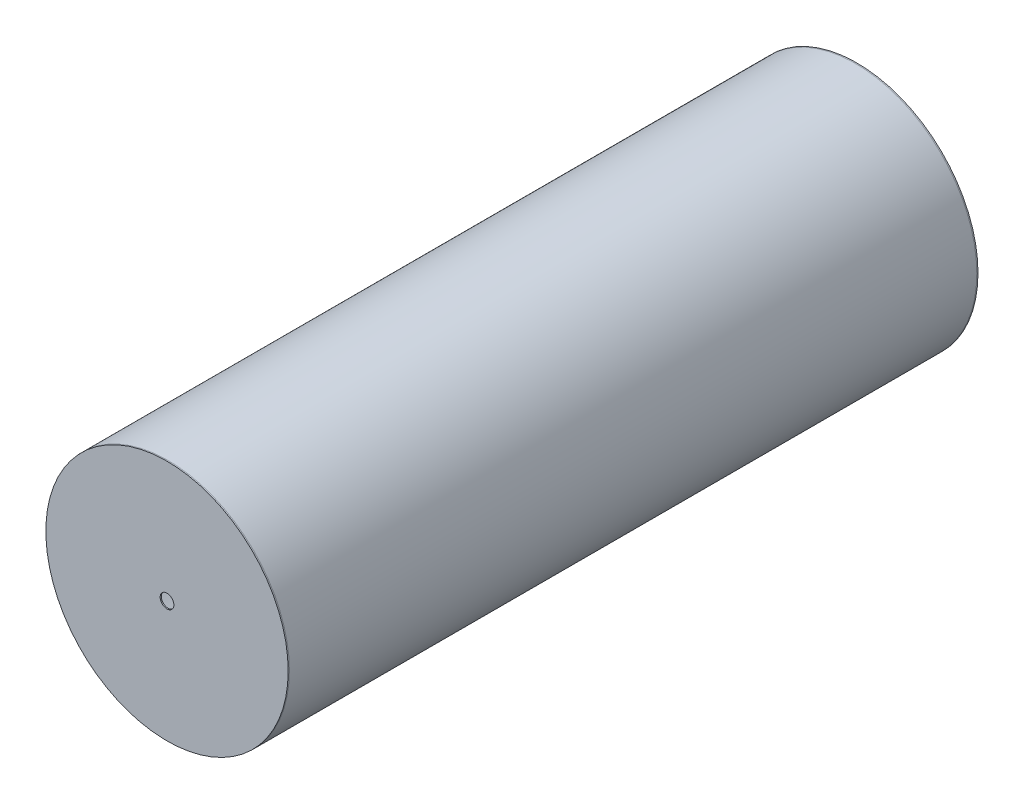
SolidWorks part; units mm, degrees
ref_plane "Front Plane" through (0, 0, 0) normal (0, 0, 1) x (1, 0, 0)
ref_plane "Top Plane" through (0, 0, 0) normal (0, 1, 0) x (1, 0, 0)
ref_plane "Right Plane" through (0, 0, 0) normal (1, 0, 0) x (0, 0, -1)
sketch "Sketch1" plane through (0, 0, 0) normal (0, 0, 1) x (1, 0, 0)
  circle A0 centre (0, 0) radius 202
  dimension "D1" = 404
extrude "Boss-Extrude1" add sketch "Sketch1" along normal blind 2
sketch "Sketch2" plane through (0, 0, 2) normal (0, 0, 1) x (1, 0, 0)
  circle A0 centre (0, 0) radius 200
  circle A1 centre (0, 0) radius 202
  dimension "D1" = 404
  dimension "D2" = 400
extrude "Boss-Extrude2" add sketch "Sketch2" along normal blind 1145.92 separate body
sketch "Sketch4" plane through (0, 0, 1147.92) normal (0, 0, 1) x (1, 0, 0)
  circle A0 centre (0, 0) radius 202
  dimension "D1" = 404
extrude "Boss-Extrude4" add sketch "Sketch4" along normal blind 2 separate body
sketch "Sketch5" plane through (0, 0, 1149.92) normal (0, 0, 1) x (1, 0, 0)
  circle A0 centre (0, 0) radius 11.45
  dimension "D1" = 22.9
extrude "Cut-Extrude1" cut sketch "Sketch5" against normal through all
sketch "Sketch6" plane through (0, 0, 0) normal (0, 1, 0) x (1, 0, 0)
  line L0 (0, -1147.92) -> (0, 0) construction
  line L1 (-202, -1147.92) -> (202, -1147.92) construction
  circle A0 centre (-50, -573.96) radius 11.45
  circle A1 centre (50, -573.96) radius 11.45
  dimension "D1" = 22.9
  dimension "D2" = 22.9
  dimension "D3" = 50
  dimension "D4" = 50
extrude "Cut-Extrude2" [suppressed] cut sketch "Sketch6" against normal through all
ref_plane "Plane1" through (0, -202, 0) normal (0, -1, 0) x (-1, 0, 0)
sketch "Sketch8" [suppressed] plane through (0, -202, 0) normal (0, -1, 0) x (-1, 0, 0)
  circle A0 centre (50, -573.96) radius 11.45
  circle A1 centre (50, -573.96) radius 12
  circle A3 centre (-50, -573.96) radius 11.45
  circle A4 centre (-50, -573.96) radius 12
  dimension "D1" = 24
  dimension "D2" = 24
extrude "Boss-Extrude5" [suppressed] add sketch "Sketch8" along normal blind 150 and the other way up to surface
sketch "Sketch9" [suppressed] plane through (0, -352, 0) normal (0, -1, 0) x (1, 0, 0)
  circle A0 centre (-50, 573.96) radius 11.45
extrude "Boss-Extrude6" [suppressed] add sketch "Sketch9" against normal blind 2 separate body
sketch "Sketch10" [suppressed] plane through (0, -352, 0) normal (0, -1, 0) x (1, 0, 0)
  circle A0 centre (50, 573.96) radius 11.45
extrude "Boss-Extrude7" [suppressed] add sketch "Sketch10" against normal blind 2
